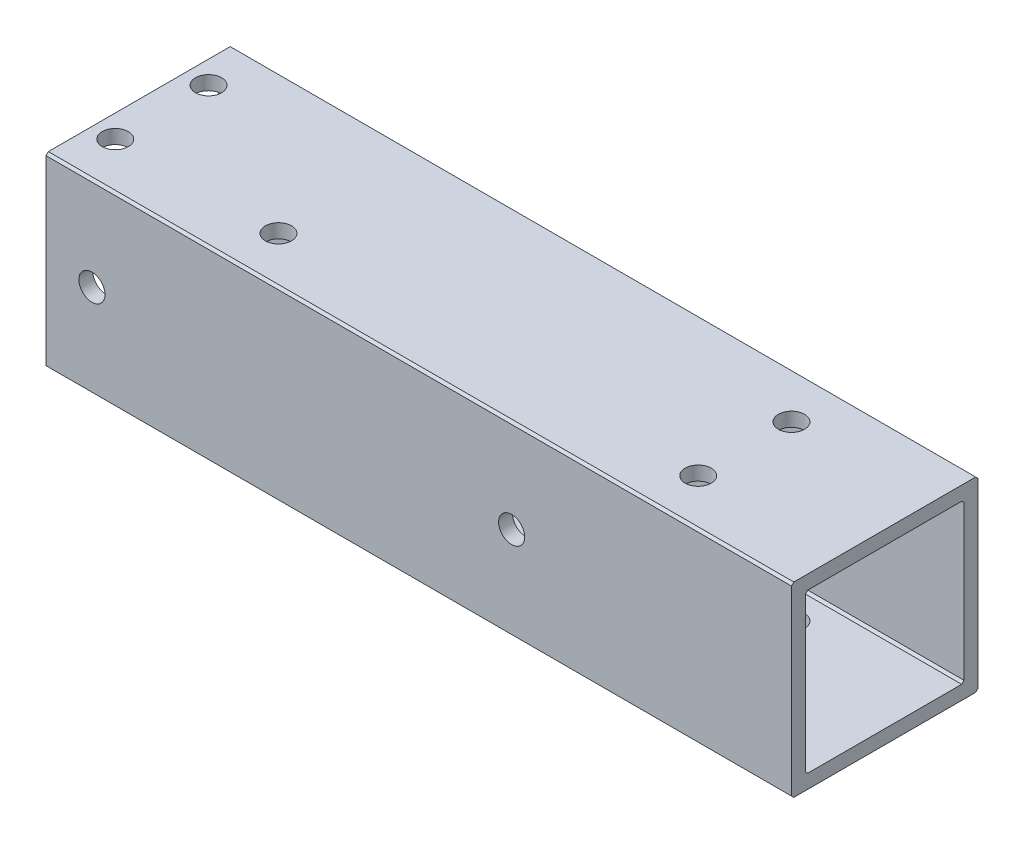
SolidWorks part; units mm, degrees
ref_plane "Front Plane" through (0, 0, 0) normal (0, 0, 1) x (1, 0, 0)
ref_plane "Top Plane" through (0, 0, 0) normal (0, 1, 0) x (1, 0, 0)
ref_plane "Right Plane" through (0, 0, 0) normal (1, 0, 0) x (0, 0, -1)
ref_plane "Plane1" through (0, 142, 0) normal (0, 1, 0) x (1, 0, 0)
sketch "Sketch1" plane through (0, 142, 0) normal (0, 1, 0) x (1, 0, 0)
  line L0 (250, -140) -> (250, -100)
  line L1 (250, -100) -> (90.15, -100)
  line L2 (90.15, -100) -> (90.15, -140)
  line L3 (90.15, -140) -> (250, -140)
extrude "Boss-Extrude1" add sketch "Sketch1" against normal blind 40
sketch "Sketch2" plane through (90.15, 0, 0) normal (-1, 0, 0) x (0, 0, 1)
  line L0 (103, 105) -> (137, 105)
  line L1 (137, 105) -> (137, 139)
  line L2 (137, 139) -> (103, 139)
  line L3 (103, 139) -> (103, 105)
extrude "Cut-Extrude1" cut sketch "Sketch2" against normal through all
hole_wizard "Ø5.6 (5.6) Diameter Hole1" positions "Sketch4" profile "Sketch3" hole size "Ø5.6" standard "ANSI Metric"
sketch "Sketch4" plane through (0, 105, 0) normal (0, 1, 0) x (1, 0, 0)
  point P0 (220, -130)
  point P1 (220, -110)
  point P2 (130, -130)
  point P3 (95, -130)
  point P4 (95, -110)
sketch "Sketch3" plane through (220, 105, 130) normal (1, 0, 0) x (0, 0, 1)
  line L0 (0, 0) -> (0, 3)
  line L1 (0, 3) -> (2.8, 3)
  line L2 (2.8, 3) -> (2.8, 0)
  line L5 (2.8, 0) -> (0, 0)
  line L11 (0, -6.35) -> (0, 107.95) construction
  dimension "Thru Hole Dia." = 5.6
  dimension "Thru Hole Depth" = 3
hole_wizard "Ø5.6 (5.6) Diameter Hole2" positions "Sketch6" profile "Sketch5" hole size "Ø5.6" standard "ANSI Metric"
sketch "Sketch6" plane through (0, 0, 100) normal (0, 0, -1) x (-1, 0, 0)
  point P0 (-190, 122)
  point P1 (-100, 122)
sketch "Sketch5" plane through (190, 122, 100) normal (1, 0, 0) x (0, 1, 0)
  line L0 (0, 0) -> (0, 3)
  line L1 (0, 3) -> (2.8, 3)
  line L2 (2.8, 3) -> (2.8, 0)
  line L5 (2.8, 0) -> (0, 0)
  line L11 (0, -6.35) -> (0, 107.95) construction
  dimension "Thru Hole Dia." = 5.6
  dimension "Thru Hole Depth" = 3
hole_wizard "Ø5.6 (5.6) Diameter Hole3" positions "Sketch8" profile "Sketch7" hole size "Ø5.6" standard "ANSI Metric"
sketch "Sketch8" plane through (0, 0, 137) normal (0, 0, -1) x (-1, 0, 0)
  point P0 (-190, 122)
  point P1 (-100, 122)
sketch "Sketch7" plane through (190, 122, 137) normal (1, 0, 0) x (0, 1, 0)
  line L0 (0, 0) -> (0, 3)
  line L1 (0, 3) -> (2.8, 3)
  line L2 (2.8, 3) -> (2.8, 0)
  line L5 (2.8, 0) -> (0, 0)
  line L11 (0, -6.35) -> (0, 107.95) construction
  dimension "Thru Hole Dia." = 5.6
  dimension "Thru Hole Depth" = 3
hole_wizard "Ø5.6 (5.6) Diameter Hole4" positions "Sketch10" profile "Sketch9" hole size "Ø5.6" standard "ANSI Metric"
sketch "Sketch10" plane through (0, 142, 0) normal (0, 1, 0) x (1, 0, 0)
  point P0 (220, -130)
  point P1 (220, -110)
  point P2 (130, -130)
  point P3 (95, -130)
  point P4 (95, -110)
sketch "Sketch9" plane through (220, 142, 130) normal (1, 0, 0) x (0, 0, 1)
  line L0 (0, 0) -> (0, 40)
  line L1 (0, 40) -> (2.8, 40)
  line L2 (2.8, 40) -> (2.8, 0)
  line L5 (2.8, 0) -> (0, 0)
  line L11 (0, -6.35) -> (0, 107.95) construction
  dimension "Thru Hole Dia." = 5.6
  dimension "Thru Hole Depth" = 40
chamfer "Chamfer1" distance 0.5 angle 45 8 edges at (170.075, 102, 100) (170.075, 142, 100) (170.075, 142, 140) (170.075, 139, 137) (170.075, 102, 140) (170.075, 105, 103) (170.075, 105, 137) (170.075, 139, 103)
